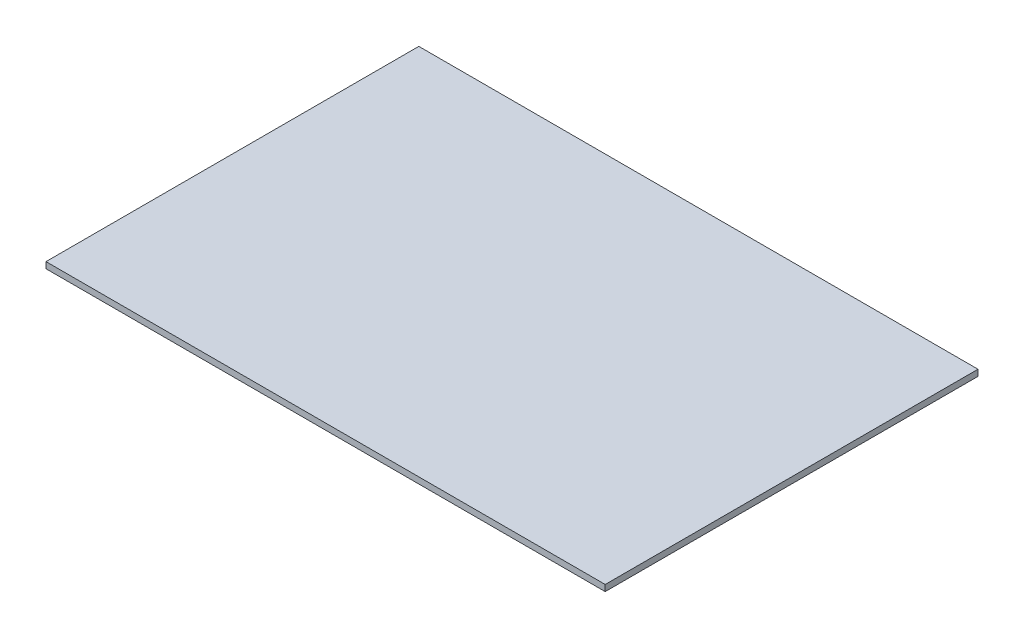
SolidWorks part; units mm, degrees
ref_plane "Front Plane" through (0, 0, 0) normal (0, 0, 1) x (1, 0, 0)
ref_plane "Top Plane" through (0, 0, 0) normal (0, 1, 0) x (1, 0, 0)
ref_plane "Right Plane" through (0, 0, 0) normal (1, 0, 0) x (0, 0, -1)
sketch "Sketch1" plane through (0, 0, 0) normal (0, 1, 0) x (1, 0, 0)
  line L1 (-45, 30) -> (45, 30)
  line L2 (-45, 30) -> (-45, -30)
  line L3 (-45, -30) -> (45, -30)
  line L4 (45, 30) -> (45, -30)
  point P4 (0, -30)
  point P5 (45, 0)
  dimension "D1" = 90
  dimension "D2" = 60
extrude "Boss-Extrude1" add sketch "Sketch1" along normal blind 1
